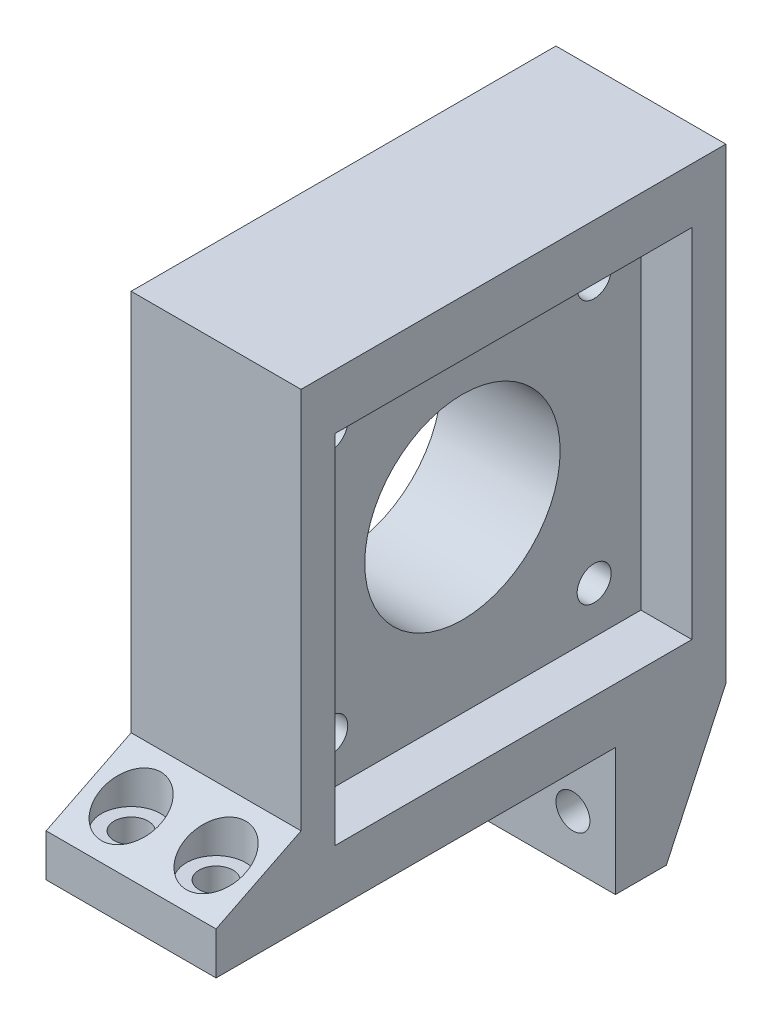
SolidWorks part; units mm, degrees
ref_plane "Front Plane" through (0, 0, 0) normal (0, 0, 1) x (1, 0, 0)
ref_plane "Top Plane" through (0, 0, 0) normal (0, 1, 0) x (1, 0, 0)
ref_plane "Right Plane" through (0, 0, 0) normal (1, 0, 0) x (0, 0, -1)
sketch "Sketch1" plane through (0, 0, 0) normal (0, 1, 0) x (1, 0, 0)
  line L1 (0, 0) -> (-20, 0)
  line L2 (0, 0) -> (0, -50)
  line L3 (0, -50) -> (-20, -50)
  line L4 (-20, 0) -> (-20, -50)
  dimension "D1" = 20
  dimension "D2" = 50
extrude "Boss-Extrude1" add sketch "Sketch1" along normal blind 70
sketch "Sketch2" plane through (0, 0, 0) normal (1, 0, 0) x (0, 0, -1)
  line L0 (-50, 70) -> (0, 70) construction
  line L1 (0, 70) -> (0, 0) construction
  line L2 (0, 42.5) -> (-50, 42.5) construction
  line L3 (-25, 70) -> (-25, 0) construction
  line L4 (-25, 70) -> (-25, 0) construction
  line L7 (-50, 70) -> (-50, 0) construction
  circle A0 centre (-9.5, 58) radius 2
  circle A4 centre (-25, 42.5) radius 11.5
  circle A5 centre (-9.5, 27) radius 2
  circle A8 centre (-40.5, 27) radius 2
  circle A9 centre (-40.5, 58) radius 2
  dimension "D1" = 4
  dimension "D2" = 12
  dimension "D3" = 15.5
  dimension "D6" = 23
  dimension "D7" = 0
  dimension "D8" = 0
  dimension "D4" = 15.5
  dimension "D5" = 0
extrude "Cut-Extrude2" cut sketch "Sketch2" against normal blind 60
sketch "Sketch4" plane through (0, 0, 0) normal (1, 0, 0) x (0, 0, -1)
  line L1 (-50, 0) -> (-13, 0)
  line L2 (-50, 0) -> (-50, 15)
  line L3 (-50, 15) -> (-13, 15)
  line L4 (-13, 0) -> (-13, 15)
  circle A0 centre (-25, 42.5) radius 11.5 construction
  dimension "D1" = 15
  dimension "D2" = 12
extrude "Cut-Extrude3" cut sketch "Sketch4" against normal blind 60
sketch "Sketch8" plane through (0, 0, 0) normal (0, 0, -1) x (-1, 0, 0)
  line L0 (0, 0) -> (20, 0) construction
  line L1 (20, 70) -> (20, 0) construction
  line L2 (0, 70) -> (0, 0) construction
  circle A0 centre (15, 6) radius 2
  circle A1 centre (5, 6) radius 2
  dimension "D1" = 4
  dimension "D2" = 6
  dimension "D3" = 5
  dimension "D4" = 4
  dimension "D5" = 0
  dimension "D6" = 5
extrude "Cut-Extrude5" cut sketch "Sketch8" against normal blind 15
sketch "Sketch9" plane through (0, 0, 0) normal (1, 0, 0) x (0, 0, -1)
  line L0 (0, 42.5) -> (-50, 42.5) construction
  line L1 (-4, 63.5) -> (-46, 63.5)
  line L2 (-4, 63.5) -> (-4, 21.5)
  line L3 (-4, 21.5) -> (-46, 21.5)
  line L4 (-46, 63.5) -> (-46, 21.5)
  line L5 (0, 70) -> (0, 0) construction
  line L6 (-50, 70) -> (-50, 15) construction
  line L7 (-25, 70) -> (-25, 15) construction
  line L8 (-50, 70) -> (0, 70) construction
  line L9 (-13, 15) -> (-50, 15) construction
  circle A0 centre (-25, 42.5) radius 11.5 construction
  dimension "D1" = 0
  dimension "D2" = 42
  dimension "D3" = 21
  dimension "D4" = 42
  dimension "D5" = 21
  dimension "D6" = 0
extrude "Cut-Extrude6" cut sketch "Sketch9" against normal blind 6
sketch "Sketch11" plane through (0, 0, 0) normal (1, 0, 0) x (0, 0, -1)
  line L7 (-7, 0) -> (0, 0)
  line L8 (-13, 0) -> (0, 0) construction
  line L9 (0, 0) -> (0, 15)
  line L10 (0, 70) -> (0, 0) construction
  line L11 (0, 15) -> (-7, 0)
  line L12 (-13, 15) -> (-50, 15) construction
  dimension "D1" = 0
  dimension "D2" = 6
extrude "Cut-Extrude8" cut sketch "Sketch11" against normal blind 30
sketch "Sketch12" plane through (0, 0, 50) normal (0, 0, 1) x (1, 0, 0)
  line L0 (-20, 70) -> (-20, 15) construction
  line L1 (0, 15) -> (-20, 15)
  line L2 (0, 15) -> (0, 20)
  line L3 (0, 20) -> (-20, 20)
  line L4 (-20, 15) -> (-20, 20)
  dimension "D1" = 5
extrude "Boss-Extrude2" add sketch "Sketch12" along normal blind 10
sketch "Sketch14" plane through (0, 0, 0) normal (1, 0, 0) x (0, 0, -1)
  line L0 (-50, 20) -> (-60, 20)
  line L1 (-60, 20) -> (-50, 20) construction
  line L2 (-60, 20) -> (-50, 25)
  line L3 (-50, 70) -> (-50, 20) construction
  line L4 (-50, 25) -> (-50, 20)
  dimension "D1" = 5
extrude "Boss-Extrude3" add sketch "Sketch14" against normal up to vertex (20 mm away)
sketch "Sketch15" plane through (0, 15, 0) normal (0, -1, 0) x (-1, 0, 0)
  line L0 (0, -13) -> (0, -60) construction
  line L1 (20, -13) -> (20, -60) construction
  line L2 (20, -60) -> (0, -60) construction
  circle A0 centre (5, -55) radius 2
  circle A1 centre (15, -55) radius 2
  dimension "D1" = 4
  dimension "D2" = 4
  dimension "D3" = 5
  dimension "D4" = 5
  dimension "D5" = 5
  dimension "D6" = 5
extrude "Cut-Extrude9" cut sketch "Sketch15" against normal blind 10
sketch "Sketch17" plane through (0, 0, 0) normal (0, 0, -1) x (-1, 0, 0)
  circle A0 centre (15, 6) radius 3.5
  circle A1 centre (5, 6) radius 3.5
  dimension "D1" = 7
  dimension "D2" = 7
extrude "Cut-Extrude11" cut sketch "Sketch17" against normal blind 8
sketch "Sketch18" plane through (0, 70, 0) normal (0, 1, 0) x (1, 0, 0)
  circle A0 centre (-15, -55) radius 3.5
  circle A1 centre (-5, -55) radius 3.5
  dimension "D1" = 7
  dimension "D2" = 7
extrude "Cut-Extrude12" cut sketch "Sketch18" against normal blind 50
